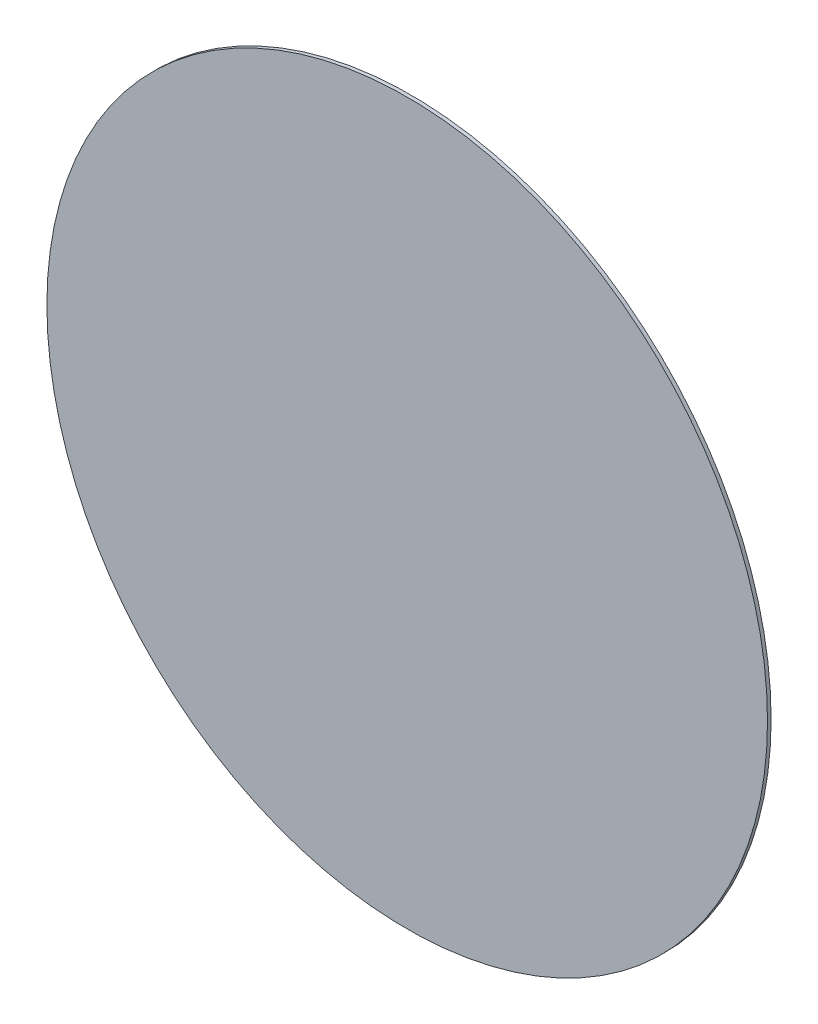
SolidWorks part; units mm, degrees
ref_plane "Front Plane" through (0, 0, 0) normal (0, 0, 1) x (1, 0, 0)
ref_plane "Top Plane" through (0, 0, 0) normal (0, 1, 0) x (1, 0, 0)
ref_plane "Right Plane" through (0, 0, 0) normal (1, 0, 0) x (0, 0, -1)
sketch "Sketch1" plane through (0, 0, 0) normal (0, 0, 1) x (1, 0, 0)
  circle A0 centre (0, 0) radius 6.35
  dimension "D1" = 12.7
extrude "Boss-Extrude1" add sketch "Sketch1" along normal blind 0.0635
